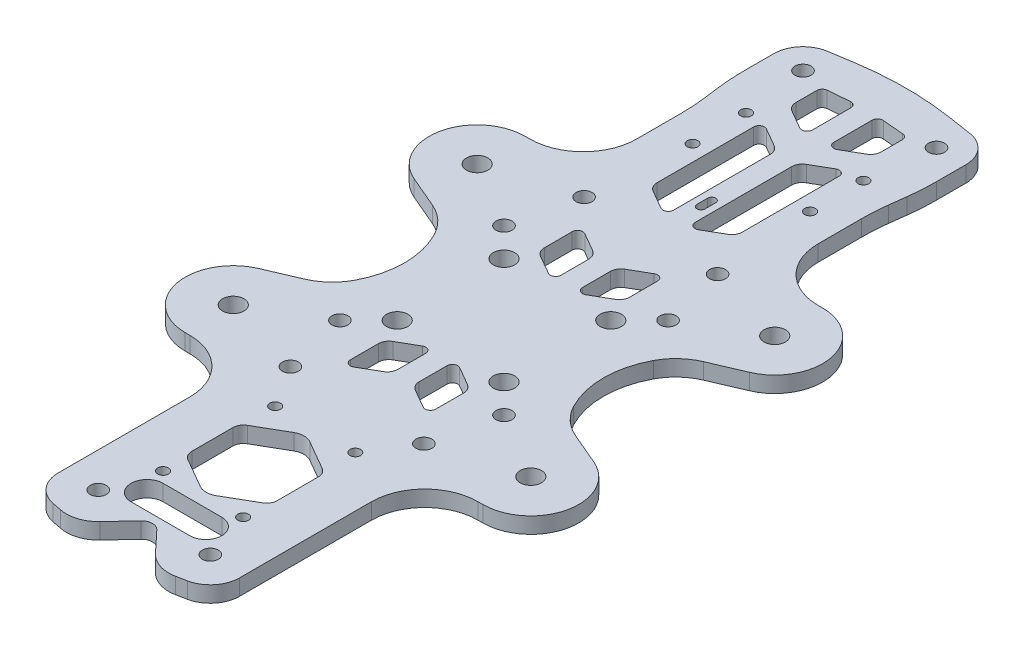
SolidWorks part; units mm, degrees
other "Markup1"
sketch "Sketch3" plane through (-36.8644, 3, -75.3176) normal (0, 1, 0) x (1, 0, 0)
material "Thornel Mat VMA"
ref_plane "Front Plane" through (0, 0, 0) normal (0, 0, 1) x (1, 0, 0)
ref_plane "Top Plane" through (0, 0, 0) normal (0, 1, 0) x (1, 0, 0)
ref_plane "Right Plane" through (0, 0, 0) normal (1, 0, 0) x (0, 0, -1)
sketch "Sketch1" plane through (0, 0, 0) normal (0, 1, 0) x (1, 0, 0)
  line L0 (7.0144, -13.8425) -> (3.5179, -11.8157)
  line L1 (-1.9927, -17.8721) -> (-1.9837, -12.6721)
  line L2 (-6.9856, 13.8181) -> (-3.4821, 11.8035)
  line L3 (2.0122, 17.9008) -> (2.0164, 12.6801)
  line L4 (2, 51.8812) -> (2, 33.7679)
  line L5 (-7, 34.9226) -> (-3.5, 32.9019)
  line L6 (3.5, 58.9019) -> (7, 60.9226)
  line L7 (-7, 60.9226) -> (-3.5, 58.9019)
  line L8 (-1.5, -37.866) -> (-7, -41.0415)
  line L9 (-6.6638, -69.1081) -> (-2.9181, -65.1127)
  line L10 (2.0164, -12.6801) -> (2.0122, -17.9008)
  line L11 (3, -19.6132) -> (6.5, -21.634)
  line L12 (8.002, -20.7686) -> (8.0113, -15.5764)
  line L13 (-3.4821, -11.8035) -> (-6.9856, -13.8181)
  line L14 (-7.9886, -15.5483) -> (-7.9977, -20.7675)
  line L15 (-6.5, -21.634) -> (-3, -19.6133)
  line L16 (-1.9837, 12.6721) -> (-1.9927, 17.8721)
  line L17 (-3, 19.6133) -> (-6.5, 21.634)
  line L18 (-7.9977, 20.7675) -> (-7.9886, 15.5483)
  line L19 (3.5179, 11.8157) -> (7.0144, 13.8425)
  line L20 (8.0113, 15.5764) -> (8.002, 20.7686)
  line L21 (6.5, 21.634) -> (3, 19.6132)
  line L22 (3.5, 32.9019) -> (7, 34.9226)
  line L23 (8, 36.6547) -> (8, 54.7679)
  line L24 (6.5, 55.634) -> (3, 53.6132)
  line L25 (-2, 33.7679) -> (-2, 51.8812)
  line L26 (-3, 53.6133) -> (-6.5, 55.634)
  line L27 (-8, 54.7679) -> (-8, 36.6546)
  line L28 (8, 62.6547) -> (8, 66.5946)
  line L29 (7.0872, 67.5908) -> (3.0872, 67.9408)
  line L30 (2, 66.9446) -> (2, 59.7679)
  line L31 (-2, 59.7679) -> (-2, 66.9446)
  line L32 (-3.0872, 67.9408) -> (-7.0872, 67.5908)
  line L33 (-8, 66.5946) -> (-8, 62.6547)
  line L34 (-8, -42.7735) -> (-8, -50.4641)
  line L35 (-7, -52.1962) -> (-1.5, -55.3716)
  line L36 (1.5, -55.3716) -> (7, -52.1962)
  line L37 (8, -50.4641) -> (8, -42.7735)
  line L38 (7, -41.0415) -> (1.5, -37.866)
  line L39 (-12.1839, -69.9325) -> (-10.3636, -70.2952)
  line L40 (-15, -41.84) -> (-15, -66.5)
  line L41 (-27.8644, -29.84) -> (-27, -29.84)
  line L42 (-24.6147, -13.8367) -> (-30.6171, -16.404)
  line L43 (-30.6171, 16.404) -> (-24.6147, 13.8367)
  line L44 (-26.9944, 29.84) -> (-27.8644, 29.84)
  line L45 (-14.9906, 49.9801) -> (-14.9944, 41.8344)
  line L46 (-15.6838, 58.0267) -> (-15.3029, 54.9969)
  line L47 (-16, 68.4976) -> (-15.9961, 62.9879)
  line L48 (-8.6637, 72.6434) -> (-13.0415, 71.9578)
  line L49 (13.0415, 71.9578) -> (8.6635, 72.6434)
  line L50 (15.9961, 62.9879) -> (15.9999, 68.4976)
  line L51 (15.3029, 54.9969) -> (15.6838, 58.0267)
  line L52 (14.9944, 41.8344) -> (14.9906, 49.98)
  line L53 (27.8644, 29.84) -> (26.9944, 29.84)
  line L54 (24.6147, 13.8367) -> (30.6171, 16.404)
  line L55 (30.6171, -16.404) -> (24.6147, -13.8367)
  line L56 (27, -29.84) -> (27.8644, -29.84)
  line L57 (15, -66.5) -> (15, -41.84)
  line L58 (10.3636, -70.2952) -> (12.1839, -69.9325)
  line L59 (2.9181, -65.1127) -> (6.6638, -69.1081)
  circle A0 centre (15.365, 15.365) radius 1.5
  circle A1 centre (15.365, -15.365) radius 1.5
  circle A2 centre (-15.365, -15.365) radius 1.5
  circle A3 centre (-15.365, 15.365) radius 1.5
  circle A4 centre (27.8644, -22.84) radius 2
  circle A5 centre (27.8644, 22.84) radius 2
  circle A6 centre (10.5, -65.5) radius 1.5
  circle A7 centre (-10, 10) radius 2
  circle A8 centre (-10, -10) radius 2
  circle A9 centre (-10.5, -65.5) radius 1.5
  circle A10 centre (-27.8644, -22.84) radius 2
  circle A11 centre (-27.8644, 22.84) radius 2
  circle A12 centre (12.5, 68.5) radius 1.5
  circle A13 centre (-12.5, 68.5) radius 1.5
  circle A14 centre (-10, -36.5) radius 1
  circle A15 centre (12.5, 27.5) radius 1.5
  circle A16 centre (-10, -56.5) radius 1
  circle A17 centre (-12.5, 27.5) radius 1.5
  circle A18 centre (12.5, -27.5) radius 1.5
  circle A19 centre (10, -36.5) radius 1
  circle A20 centre (-12.5, -27.5) radius 1.5
  circle A21 centre (10, -56.5) radius 1
  circle A22 centre (10, 10) radius 2
  circle A23 centre (10, -10) radius 2
  arc A24 (3.5179, -11.8157) -> (2.0164, -12.6801) centre (3.0164, -12.6808) ccw
  arc A25 (2.0122, -17.9008) -> (3, -19.6132) centre (3.9878, -17.9024) ccw
  arc A26 (6.5, -21.634) -> (8.002, -20.7686) centre (7.0007, -20.7668) ccw
  arc A27 (8.0113, -15.5764) -> (7.0144, -13.8425) centre (6.0113, -15.5728) ccw
  arc A28 (-1.9837, -12.6721) -> (-3.4821, -11.8035) centre (-2.9836, -12.6704) ccw
  arc A29 (-6.9856, -13.8181) -> (-7.9886, -15.5483) centre (-5.9887, -15.5518) ccw
  arc A30 (-7.9977, -20.7675) -> (-6.5, -21.634) centre (-6.9992, -20.7693) ccw
  arc A31 (-3, -19.6133) -> (-1.9927, -17.8721) centre (-4.0073, -17.8686) ccw
  arc A32 (-3.4821, 11.8035) -> (-1.9837, 12.6721) centre (-2.9836, 12.6704) ccw
  arc A33 (-1.9927, 17.8721) -> (-3, 19.6133) centre (-4.0073, 17.8686) ccw
  arc A34 (-6.5, 21.634) -> (-7.9977, 20.7675) centre (-6.9992, 20.7693) ccw
  arc A35 (-7.9886, 15.5483) -> (-6.9856, 13.8181) centre (-5.9887, 15.5518) ccw
  arc A36 (2.0164, 12.6801) -> (3.5179, 11.8157) centre (3.0164, 12.6808) ccw
  arc A37 (7.0144, 13.8425) -> (8.0113, 15.5764) centre (6.0113, 15.5728) ccw
  arc A38 (8.002, 20.7686) -> (6.5, 21.634) centre (7.0007, 20.7668) ccw
  arc A39 (3, 19.6132) -> (2.0122, 17.9008) centre (3.9878, 17.9024) ccw
  arc A40 (2, 33.7679) -> (3.5, 32.9019) centre (3, 33.7679) ccw
  arc A41 (7, 34.9226) -> (8, 36.6547) centre (6, 36.6547) ccw
  arc A42 (8, 54.7679) -> (6.5, 55.634) centre (7, 54.7679) ccw
  arc A43 (3, 53.6132) -> (2, 51.8812) centre (4, 51.8812) ccw
  arc A44 (-3.5, 32.9019) -> (-2, 33.7679) centre (-3, 33.7679) ccw
  arc A45 (-2, 51.8812) -> (-3, 53.6133) centre (-4, 51.8812) ccw
  arc A46 (-6.5, 55.634) -> (-8, 54.7679) centre (-7, 54.7679) ccw
  arc A47 (-8, 36.6546) -> (-7, 34.9226) centre (-6, 36.6546) ccw
  arc A48 (7, 60.9226) -> (8, 62.6547) centre (6, 62.6547) ccw
  arc A49 (8, 66.5946) -> (7.0872, 67.5908) centre (7, 66.5946) ccw
  arc A50 (3.0872, 67.9408) -> (2, 66.9446) centre (3, 66.9446) ccw
  arc A51 (2, 59.7679) -> (3.5, 58.9019) centre (3, 59.7679) ccw
  arc A52 (-3.5, 58.9019) -> (-2, 59.7679) centre (-3, 59.7679) ccw
  arc A53 (-2, 66.9446) -> (-3.0872, 67.9408) centre (-3, 66.9446) ccw
  arc A54 (-7.0872, 67.5908) -> (-8, 66.5946) centre (-7, 66.5946) ccw
  arc A55 (-8, 62.6547) -> (-7, 60.9226) centre (-6, 62.6547) ccw
  arc A56 (-7, -41.0415) -> (-8, -42.7735) centre (-6, -42.7735) ccw
  arc A57 (-8, -50.4641) -> (-7, -52.1962) centre (-6, -50.4641) ccw
  arc A58 (-1.5, -55.3716) -> (1.5, -55.3716) centre (0, -52.7735) ccw
  arc A59 (7, -52.1962) -> (8, -50.4641) centre (6, -50.4641) ccw
  arc A60 (8, -42.7735) -> (7, -41.0415) centre (6, -42.7735) ccw
  arc A61 (1.5, -37.866) -> (-1.5, -37.866) centre (0, -40.4641) ccw
  arc A62 (-10.3636, -70.2952) -> (-6.6638, -69.1081) centre (-9.582, -66.3723) ccw
  arc A63 (-15, -66.5) -> (-12.1839, -69.9325) centre (-11.5, -66.5) ccw
  arc A64 (-15, -41.84) -> (-27, -29.84) centre (-27, -41.84) ccw
  arc A65 (-30.6171, -16.404) -> (-27.8644, -29.84) centre (-27.8644, -22.84) ccw
  arc A66 (-24.6147, -13.8367) -> (-18.7242, -8.4106) centre (-29.3336, -2.8035) ccw
  arc A67 (-18.7242, -8.4106) -> (-18.7242, 8.4106) centre (-34.6384, 0) ccw
  arc A68 (-18.7242, 8.4106) -> (-24.6147, 13.8367) centre (-29.3336, 2.8035) ccw
  arc A69 (-27.8644, 29.84) -> (-30.6171, 16.404) centre (-27.8644, 22.84) ccw
  arc A70 (-26.9944, 29.84) -> (-14.9944, 41.8344) centre (-26.9944, 41.84) ccw
  arc A71 (-14.9906, 49.9801) -> (-15.3029, 54.9969) centre (-54.9906, 50.008) ccw
  arc A72 (-15.9961, 62.9879) -> (-15.6838, 58.0267) centre (24.0039, 63.0156) ccw
  arc A73 (-13.0415, 71.9578) -> (-16, 68.4976) centre (-12.5, 68.5) ccw
  arc A74 (8.6635, 72.6434) -> (-8.6637, 72.6434) centre (-0.0001, 17.3176) ccw
  arc A75 (15.9999, 68.4976) -> (13.0415, 71.9578) centre (12.5, 68.5) ccw
  arc A76 (15.6838, 58.0267) -> (15.9961, 62.9879) centre (-24.0039, 63.0156) ccw
  arc A77 (15.3029, 54.9969) -> (14.9906, 49.98) centre (54.9906, 50.008) ccw
  arc A78 (14.9944, 41.8344) -> (26.9944, 29.84) centre (26.9944, 41.84) ccw
  arc A79 (30.6171, 16.404) -> (27.8644, 29.84) centre (27.8644, 22.84) ccw
  arc A80 (24.6147, 13.8367) -> (18.7242, 8.4106) centre (29.3336, 2.8035) ccw
  arc A81 (18.7242, 8.4106) -> (18.7242, -8.4106) centre (34.6384, 0) ccw
  arc A82 (18.7242, -8.4106) -> (24.6147, -13.8367) centre (29.3336, -2.8035) ccw
  arc A83 (27.8644, -29.84) -> (30.6171, -16.404) centre (27.8644, -22.84) ccw
  arc A84 (27, -29.84) -> (15, -41.84) centre (27, -41.84) ccw
  arc A85 (12.1839, -69.9325) -> (15, -66.5) centre (11.5, -66.5) ccw
  arc A86 (6.6638, -69.1081) -> (10.3636, -70.2952) centre (9.582, -66.3723) ccw
  arc A87 (2.9181, -65.1127) -> (-2.9181, -65.1127) centre (0, -67.8485) ccw
sketch "Sketch2" plane through (0, 0, 0) normal (0, 1, 0) x (1, 0, 0)
  line L0 (-3.5, 32.9019) -> (3.5, 32.9019) construction
  line L5 (0, 38.9019) -> (0, 36.9019) construction
  line L7 (0.75, 38.9019) -> (0.75, 36.9019)
  line L8 (-0.75, 38.9019) -> (-0.75, 36.9019)
  line L9 (0, 0) -> (-0.0001, 75.3176) construction
  line L10 (0, 0) -> (0, -65.8485) construction
  line L11 (-18.6384, 0) -> (18.6384, 0) construction
  line L12 (-5.5, -61.3485) -> (5.5, -61.3485) construction
  line L13 (-5.5, -58.3485) -> (5.5, -58.3485)
  line L14 (-5.5, -64.3485) -> (5.5, -64.3485)
  line L15 (-14.0001, 51.3176) -> (13.9999, 51.3176) construction
  line L16 (-14.0001, 64.3176) -> (13.9999, 64.3176) construction
  line L17 (-14.0001, 64.3176) -> (-14.0001, 44.3176) construction
  line L18 (-14.0001, 44.3176) -> (13.9999, 44.3176) construction
  line L19 (13.9999, 64.3176) -> (13.9999, 44.3176) construction
  line L20 (-14.0001, 64.3176) -> (13.9999, 44.3176) construction
  line L21 (-14.0001, 44.3176) -> (13.9999, 64.3176) construction
  line L22 (-11.0001, 46.3176) -> (10.9999, 46.3176) construction
  line L513 (7, -41.0415) -> (1.5, -37.866) construction
  line L514 (-1.5, -37.866) -> (-7, -41.0415) construction
  line L515 (1.5, -55.3716) -> (7, -52.1962) construction
  line L516 (8, -50.4641) -> (8, -42.7735) construction
  line L517 (-8, -42.7735) -> (-8, -50.4641) construction
  line L518 (-7, -52.1962) -> (-1.5, -55.3716) construction
  line L519 (3, -19.6132) -> (6.5, -21.634) construction
  line L520 (7.0144, -13.8425) -> (3.5179, -11.8157) construction
  line L521 (8.002, -20.7686) -> (8.0113, -15.5764) construction
  line L522 (2.0164, -12.6801) -> (2.0122, -17.9008) construction
  line L523 (-6.5, -21.634) -> (-3, -19.6133) construction
  line L524 (-7.9886, -15.5483) -> (-7.9977, -20.7675) construction
  line L525 (-3.4821, -11.8035) -> (-6.9856, -13.8181) construction
  line L526 (-1.9927, -17.8721) -> (-1.9837, -12.6721) construction
  line L527 (3.5179, 11.8157) -> (7.0144, 13.8425) construction
  line L528 (8.0113, 15.5764) -> (8.002, 20.7686) construction
  line L529 (6.5, 21.634) -> (3, 19.6132) construction
  line L530 (-3, 19.6133) -> (-6.5, 21.634) construction
  line L531 (-7.9977, 20.7675) -> (-7.9886, 15.5483) construction
  line L532 (-1.9837, 12.6721) -> (-1.9927, 17.8721) construction
  line L533 (2.0122, 17.9008) -> (2.0164, 12.6801) construction
  line L534 (-6.9856, 13.8181) -> (-3.4821, 11.8035) construction
  line L535 (13.3509, 73.9337) -> (8.9729, 74.6193)
  line L536 (-8.9731, 74.6193) -> (-13.3509, 73.9338)
  line L537 (-18, 68.4962) -> (-17.9961, 62.9865)
  line L538 (-17.6682, 57.7773) -> (-17.2873, 54.7475)
  line L539 (17.9961, 62.9865) -> (17.9999, 68.4962)
  line L540 (17.2873, 54.7474) -> (17.6682, 57.7773)
  line L541 (-16.9906, 49.981) -> (-16.9944, 41.8353)
  line L542 (16.9944, 41.8353) -> (16.9906, 49.9814)
  line L543 (27.8644, 31.84) -> (26.9944, 31.84)
  line L544 (25.4012, 11.9979) -> (31.4036, 14.5651)
  line L545 (31.4036, -14.5651) -> (25.4012, -11.9979)
  line L546 (27, -31.84) -> (27.8644, -31.84)
  line L547 (17, -66.5) -> (17, -41.84)
  line L548 (10.7545, -72.2567) -> (12.5748, -71.894)
  line L549 (1.4591, -66.4806) -> (5.2048, -70.476)
  line L550 (-5.2048, -70.476) -> (-1.4591, -66.4806)
  line L551 (-12.5748, -71.894) -> (-10.7545, -72.2567)
  line L552 (-17, -41.84) -> (-17, -66.5)
  line L553 (-27.8644, -31.84) -> (-27, -31.84)
  line L554 (-25.4012, -11.9979) -> (-31.4036, -14.5651)
  line L555 (-31.4036, 14.5651) -> (-25.4012, 11.9979)
  line L556 (-26.9944, 31.84) -> (-27.8644, 31.84)
  line L557 (13.3509, 73.9337) -> (8.9729, 74.6193)
  line L558 (-8.9731, 74.6193) -> (-13.3509, 73.9338)
  line L559 (-18, 68.4962) -> (-17.9961, 62.9865)
  line L560 (-17.6682, 57.7773) -> (-17.2873, 54.7475)
  line L561 (17.9961, 62.9865) -> (17.9999, 68.4962)
  line L562 (17.2873, 54.7474) -> (17.6682, 57.7773)
  line L563 (-16.9906, 49.981) -> (-16.9944, 41.8353)
  line L564 (16.9944, 41.8353) -> (16.9906, 49.9814)
  line L565 (27.8644, 31.84) -> (26.9944, 31.84)
  line L566 (25.4012, 11.9979) -> (31.4036, 14.5651)
  line L567 (31.4036, -14.5651) -> (25.4012, -11.9979)
  line L568 (27, -31.84) -> (27.8644, -31.84)
  line L569 (17, -66.5) -> (17, -41.84)
  line L570 (10.7545, -72.2567) -> (12.5748, -71.894)
  line L571 (1.4591, -66.4806) -> (5.2048, -70.476)
  line L572 (-5.2048, -70.476) -> (-1.4591, -66.4806)
  line L573 (-12.5748, -71.894) -> (-10.7545, -72.2567)
  line L574 (-17, -41.84) -> (-17, -66.5)
  line L575 (-27.8644, -31.84) -> (-27, -31.84)
  line L576 (-25.4012, -11.9979) -> (-31.4036, -14.5651)
  line L577 (-31.4036, 14.5651) -> (-25.4012, 11.9979)
  line L578 (-26.9944, 31.84) -> (-27.8644, 31.84)
  line L579 (3.5, 32.9019) -> (7, 34.9226) construction
  line L580 (-7, 34.9226) -> (-3.5, 32.9019) construction
  line L581 (8, 36.6547) -> (8, 54.7679) construction
  line L582 (6.5, 55.634) -> (3, 53.6132) construction
  line L583 (-3, 53.6133) -> (-6.5, 55.634) construction
  line L584 (-2, 33.7679) -> (-2, 51.8812) construction
  line L585 (2, 51.8812) -> (2, 33.7679) construction
  line L586 (-8, 54.7679) -> (-8, 36.6546) construction
  line L587 (3.5, 58.9019) -> (7, 60.9226) construction
  line L588 (8, 62.6547) -> (8, 66.5946) construction
  line L589 (7.0872, 67.5908) -> (3.0872, 67.9408) construction
  line L590 (2, 66.9446) -> (2, 59.7679) construction
  line L591 (-7, 60.9226) -> (-3.5, 58.9019) construction
  line L592 (-2, 59.7679) -> (-2, 66.9446) construction
  line L593 (-3.0872, 67.9408) -> (-7.0872, 67.5908) construction
  line L594 (-8, 66.5946) -> (-8, 62.6547) construction
  line L595 (7, -41.0415) -> (1.5, -37.866)
  line L596 (-1.5, -37.866) -> (-7, -41.0415)
  line L597 (1.5, -55.3716) -> (7, -52.1962)
  line L598 (8, -50.4641) -> (8, -42.7735)
  line L599 (-8, -42.7735) -> (-8, -50.4641)
  line L600 (-7, -52.1962) -> (-1.5, -55.3716)
  line L601 (3, -19.6132) -> (6.5, -21.634)
  line L602 (7.0144, -13.8425) -> (3.5179, -11.8157)
  line L603 (8.002, -20.7686) -> (8.0113, -15.5764)
  line L604 (2.0164, -12.6801) -> (2.0122, -17.9008)
  line L605 (-6.5, -21.634) -> (-3, -19.6133)
  line L606 (-7.9886, -15.5483) -> (-7.9977, -20.7675)
  line L607 (-3.4821, -11.8035) -> (-6.9856, -13.8181)
  line L608 (-1.9927, -17.8721) -> (-1.9837, -12.6721)
  line L609 (3.5179, 11.8157) -> (7.0144, 13.8425)
  line L610 (8.0113, 15.5764) -> (8.002, 20.7686)
  line L611 (6.5, 21.634) -> (3, 19.6132)
  line L612 (-3, 19.6133) -> (-6.5, 21.634)
  line L613 (-7.9977, 20.7675) -> (-7.9886, 15.5483)
  line L614 (-1.9837, 12.6721) -> (-1.9927, 17.8721)
  line L615 (2.0122, 17.9008) -> (2.0164, 12.6801)
  line L616 (-6.9856, 13.8181) -> (-3.4821, 11.8035)
  line L617 (3.5, 32.9019) -> (7, 34.9226)
  line L618 (-7, 34.9226) -> (-3.5, 32.9019)
  line L619 (8, 36.6547) -> (8, 54.7679)
  line L620 (6.5, 55.634) -> (3, 53.6132)
  line L621 (-3, 53.6133) -> (-6.5, 55.634)
  line L622 (-2, 33.7679) -> (-2, 51.8812)
  line L623 (2, 51.8812) -> (2, 33.7679)
  line L624 (-8, 54.7679) -> (-8, 36.6546)
  line L625 (3.5, 58.9019) -> (7, 60.9226)
  line L626 (8, 62.6547) -> (8, 66.5946)
  line L627 (7.0872, 67.5908) -> (3.0872, 67.9408)
  line L628 (2, 66.9446) -> (2, 59.7679)
  line L629 (-7, 60.9226) -> (-3.5, 58.9019)
  line L630 (-2, 59.7679) -> (-2, 66.9446)
  line L631 (-3.0872, 67.9408) -> (-7.0872, 67.5908)
  line L632 (-8, 66.5946) -> (-8, 62.6547)
  arc A1 (0.75, 38.9019) -> (-0.75, 38.9019) centre (0, 38.9019) ccw
  arc A2 (-0.75, 36.9019) -> (0.75, 36.9019) centre (0, 36.9019) ccw
  circle A3 centre (-12.5, 68.5) radius 2.75 construction
  circle A4 centre (12.4998, 68.5) radius 2.75 construction
  circle A5 centre (-7.5, -35.3485) radius 1
  circle A6 centre (-7.5, -56.3485) radius 1
  circle A7 centre (7.5, -35.3485) radius 1
  circle A8 centre (7.5, -56.3485) radius 1
  arc A9 (-5.5, -58.3485) -> (-5.5, -64.3485) centre (-5.5, -61.3485) ccw
  arc A10 (5.5, -64.3485) -> (5.5, -58.3485) centre (5.5, -61.3485) ccw
  circle A11 centre (-10.5, -65.5) radius 2.75 construction
  circle A12 centre (10.5, -65.5) radius 2.75 construction
  circle A16 centre (-11.0001, 46.3176) radius 1
  circle A17 centre (10.9999, 46.3176) radius 1
  circle A18 centre (10.9999, 56.3176) radius 1
  circle A19 centre (-11.0001, 56.3176) radius 1
  arc A666 (8, -42.7735) -> (7, -41.0415) centre (6, -42.7735) ccw construction
  arc A667 (1.5, -37.866) -> (-1.5, -37.866) centre (0, -40.4641) ccw construction
  arc A668 (-7, -41.0415) -> (-8, -42.7735) centre (-6, -42.7735) ccw construction
  arc A669 (-8, -50.4641) -> (-7, -52.1962) centre (-6, -50.4641) ccw construction
  arc A670 (-1.5, -55.3716) -> (1.5, -55.3716) centre (0, -52.7735) ccw construction
  arc A671 (7, -52.1962) -> (8, -50.4641) centre (6, -50.4641) ccw construction
  circle A674 centre (10.5, -65.5) radius 1.5 construction
  circle A675 centre (-10.5, -65.5) radius 1.5 construction
  arc A676 (6.5, -21.634) -> (8.002, -20.7686) centre (7.0007, -20.7668) ccw construction
  arc A677 (2.0122, -17.9008) -> (3, -19.6132) centre (3.9878, -17.9024) ccw construction
  arc A678 (3.5179, -11.8157) -> (2.0164, -12.6801) centre (3.0164, -12.6808) ccw construction
  arc A679 (8.0113, -15.5764) -> (7.0144, -13.8425) centre (6.0113, -15.5728) ccw construction
  arc A680 (-3, -19.6133) -> (-1.9927, -17.8721) centre (-4.0073, -17.8686) ccw construction
  arc A681 (-7.9977, -20.7675) -> (-6.5, -21.634) centre (-6.9992, -20.7693) ccw construction
  arc A682 (-6.9856, -13.8181) -> (-7.9886, -15.5483) centre (-5.9887, -15.5518) ccw construction
  arc A683 (-1.9837, -12.6721) -> (-3.4821, -11.8035) centre (-2.9836, -12.6704) ccw construction
  circle A684 centre (10, -10) radius 2 construction
  circle A685 centre (15.365, -15.365) radius 1.5 construction
  circle A686 centre (27.8644, -22.84) radius 2 construction
  circle A687 centre (12.5, -27.5) radius 1.5 construction
  circle A690 centre (-10, -10) radius 2 construction
  circle A691 centre (-15.365, -15.365) radius 1.5 construction
  arc A692 (8.9729, 74.6193) -> (-8.9731, 74.6193) centre (-0.0001, 17.3176) ccw
  arc A693 (-13.3509, 73.9338) -> (-18, 68.4962) centre (-12.5, 68.5) ccw
  arc A694 (-17.9961, 62.9865) -> (-17.6682, 57.7773) centre (24.0039, 63.0156) ccw
  arc A695 (17.9999, 68.4962) -> (13.3509, 73.9337) centre (12.5, 68.5) ccw
  arc A696 (17.6682, 57.7773) -> (17.9961, 62.9865) centre (-24.0039, 63.0156) ccw
  arc A697 (-16.9906, 49.981) -> (-17.2873, 54.7475) centre (-54.9906, 50.008) ccw
  arc A698 (17.2873, 54.7474) -> (16.9906, 49.9814) centre (54.9906, 50.008) ccw
  arc A699 (16.9944, 41.8353) -> (26.9944, 31.84) centre (26.9944, 41.84) ccw
  arc A700 (31.4036, 14.5651) -> (27.8644, 31.84) centre (27.8644, 22.84) ccw
  arc A701 (25.4012, 11.9979) -> (20.4924, 7.4761) centre (29.3336, 2.8035) ccw
  arc A702 (20.4924, 7.4761) -> (20.4924, -7.4761) centre (34.6384, 0) ccw
  arc A703 (20.4924, -7.4761) -> (25.4012, -11.9979) centre (29.3336, -2.8035) ccw
  arc A704 (27.8644, -31.84) -> (31.4036, -14.5651) centre (27.8644, -22.84) ccw
  arc A705 (27, -31.84) -> (17, -41.84) centre (27, -41.84) ccw
  arc A706 (12.5748, -71.894) -> (17, -66.5) centre (11.5, -66.5) ccw
  arc A707 (5.2048, -70.476) -> (10.7545, -72.2567) centre (9.582, -66.3723) ccw
  arc A708 (1.4591, -66.4806) -> (-1.4591, -66.4806) centre (0, -67.8485) ccw
  arc A709 (-10.7545, -72.2567) -> (-5.2048, -70.476) centre (-9.582, -66.3723) ccw
  arc A710 (-17, -66.5) -> (-12.5748, -71.894) centre (-11.5, -66.5) ccw
  arc A711 (-17, -41.84) -> (-27, -31.84) centre (-27, -41.84) ccw
  arc A712 (-31.4036, -14.5651) -> (-27.8644, -31.84) centre (-27.8644, -22.84) ccw
  arc A713 (-25.4012, -11.9979) -> (-20.4924, -7.4761) centre (-29.3336, -2.8035) ccw
  arc A714 (-20.4924, -7.4761) -> (-20.4924, 7.4761) centre (-34.6384, 0) ccw
  arc A715 (-20.4924, 7.4761) -> (-25.4012, 11.9979) centre (-29.3336, 2.8035) ccw
  arc A716 (-27.8644, 31.84) -> (-31.4036, 14.5651) centre (-27.8644, 22.84) ccw
  arc A717 (-26.9944, 31.84) -> (-16.9944, 41.8353) centre (-26.9944, 41.84) ccw
  arc A718 (8.9729, 74.6193) -> (-8.9731, 74.6193) centre (-0.0001, 17.3176) ccw
  arc A719 (-13.3509, 73.9338) -> (-18, 68.4962) centre (-12.5, 68.5) ccw
  arc A720 (-17.9961, 62.9865) -> (-17.6682, 57.7773) centre (24.0039, 63.0156) ccw
  arc A721 (17.9999, 68.4962) -> (13.3509, 73.9337) centre (12.5, 68.5) ccw
  arc A722 (17.6682, 57.7773) -> (17.9961, 62.9865) centre (-24.0039, 63.0156) ccw
  arc A723 (-16.9906, 49.981) -> (-17.2873, 54.7475) centre (-54.9906, 50.008) ccw
  arc A724 (17.2873, 54.7474) -> (16.9906, 49.9814) centre (54.9906, 50.008) ccw
  arc A725 (16.9944, 41.8353) -> (26.9944, 31.84) centre (26.9944, 41.84) ccw
  arc A726 (31.4036, 14.5651) -> (27.8644, 31.84) centre (27.8644, 22.84) ccw
  arc A727 (25.4012, 11.9979) -> (20.4924, 7.4761) centre (29.3336, 2.8035) ccw
  arc A728 (20.4924, 7.4761) -> (20.4924, -7.4761) centre (34.6384, 0) ccw
  arc A729 (20.4924, -7.4761) -> (25.4012, -11.9979) centre (29.3336, -2.8035) ccw
  arc A730 (27.8644, -31.84) -> (31.4036, -14.5651) centre (27.8644, -22.84) ccw
  arc A731 (27, -31.84) -> (17, -41.84) centre (27, -41.84) ccw
  arc A732 (12.5748, -71.894) -> (17, -66.5) centre (11.5, -66.5) ccw
  arc A733 (5.2048, -70.476) -> (10.7545, -72.2567) centre (9.582, -66.3723) ccw
  arc A734 (1.4591, -66.4806) -> (-1.4591, -66.4806) centre (0, -67.8485) ccw
  arc A735 (-10.7545, -72.2567) -> (-5.2048, -70.476) centre (-9.582, -66.3723) ccw
  arc A736 (-17, -66.5) -> (-12.5748, -71.894) centre (-11.5, -66.5) ccw
  arc A737 (-17, -41.84) -> (-27, -31.84) centre (-27, -41.84) ccw
  arc A738 (-31.4036, -14.5651) -> (-27.8644, -31.84) centre (-27.8644, -22.84) ccw
  arc A739 (-25.4012, -11.9979) -> (-20.4924, -7.4761) centre (-29.3336, -2.8035) ccw
  arc A740 (-20.4924, -7.4761) -> (-20.4924, 7.4761) centre (-34.6384, 0) ccw
  arc A741 (-20.4924, 7.4761) -> (-25.4012, 11.9979) centre (-29.3336, 2.8035) ccw
  arc A742 (-27.8644, 31.84) -> (-31.4036, 14.5651) centre (-27.8644, 22.84) ccw
  arc A743 (-26.9944, 31.84) -> (-16.9944, 41.8353) centre (-26.9944, 41.84) ccw
  circle A744 centre (-12.5, -27.5) radius 1.5 construction
  circle A745 centre (-27.8644, -22.84) radius 2 construction
  circle A746 centre (27.8644, 22.84) radius 2 construction
  circle A747 centre (15.365, 15.365) radius 1.5 construction
  circle A748 centre (10, 10) radius 2 construction
  arc A749 (2.0164, 12.6801) -> (3.5179, 11.8157) centre (3.0164, 12.6808) ccw construction
  arc A750 (7.0144, 13.8425) -> (8.0113, 15.5764) centre (6.0113, 15.5728) ccw construction
  arc A751 (8.002, 20.7686) -> (6.5, 21.634) centre (7.0007, 20.7668) ccw construction
  arc A752 (3, 19.6132) -> (2.0122, 17.9008) centre (3.9878, 17.9024) ccw construction
  arc A753 (-1.9927, 17.8721) -> (-3, 19.6133) centre (-4.0073, 17.8686) ccw construction
  arc A754 (-6.5, 21.634) -> (-7.9977, 20.7675) centre (-6.9992, 20.7693) ccw construction
  arc A755 (-7.9886, 15.5483) -> (-6.9856, 13.8181) centre (-5.9887, 15.5518) ccw construction
  arc A756 (-3.4821, 11.8035) -> (-1.9837, 12.6721) centre (-2.9836, 12.6704) ccw construction
  circle A757 centre (-10, 10) radius 2 construction
  circle A758 centre (-15.365, 15.365) radius 1.5 construction
  circle A759 centre (-27.8644, 22.84) radius 2 construction
  circle A760 centre (-12.5, 27.5) radius 1.5 construction
  circle A761 centre (12.5, 27.5) radius 1.5 construction
  arc A762 (7, 34.9226) -> (8, 36.6547) centre (6, 36.6547) ccw construction
  arc A763 (2, 33.7679) -> (3.5, 32.9019) centre (3, 33.7679) ccw construction
  arc A764 (-8, 36.6546) -> (-7, 34.9226) centre (-6, 36.6546) ccw construction
  arc A765 (-3.5, 32.9019) -> (-2, 33.7679) centre (-3, 33.7679) ccw construction
  arc A766 (8, 54.7679) -> (6.5, 55.634) centre (7, 54.7679) ccw construction
  arc A767 (3, 53.6132) -> (2, 51.8812) centre (4, 51.8812) ccw construction
  arc A768 (-2, 51.8812) -> (-3, 53.6133) centre (-4, 51.8812) ccw construction
  arc A769 (-6.5, 55.634) -> (-8, 54.7679) centre (-7, 54.7679) ccw construction
  arc A770 (2, 59.7679) -> (3.5, 58.9019) centre (3, 59.7679) ccw construction
  arc A771 (7, 60.9226) -> (8, 62.6547) centre (6, 62.6547) ccw construction
  arc A772 (8, 66.5946) -> (7.0872, 67.5908) centre (7, 66.5946) ccw construction
  arc A773 (3.0872, 67.9408) -> (2, 66.9446) centre (3, 66.9446) ccw construction
  arc A774 (-8, 62.6547) -> (-7, 60.9226) centre (-6, 62.6547) ccw construction
  arc A775 (-3.5, 58.9019) -> (-2, 59.7679) centre (-3, 59.7679) ccw construction
  arc A776 (-2, 66.9446) -> (-3.0872, 67.9408) centre (-3, 66.9446) ccw construction
  arc A777 (-7.0872, 67.5908) -> (-8, 66.5946) centre (-7, 66.5946) ccw construction
  circle A778 centre (-12.5, 68.5) radius 1.5 construction
  circle A779 centre (12.5, 68.5) radius 1.5 construction
  arc A780 (8, -42.7735) -> (7, -41.0415) centre (6, -42.7735) ccw
  arc A781 (1.5, -37.866) -> (-1.5, -37.866) centre (0, -40.4641) ccw
  arc A782 (-7, -41.0415) -> (-8, -42.7735) centre (-6, -42.7735) ccw
  arc A783 (-8, -50.4641) -> (-7, -52.1962) centre (-6, -50.4641) ccw
  arc A784 (-1.5, -55.3716) -> (1.5, -55.3716) centre (0, -52.7735) ccw
  arc A785 (7, -52.1962) -> (8, -50.4641) centre (6, -50.4641) ccw
  circle A788 centre (10.5, -65.5) radius 1.5
  circle A789 centre (-10.5, -65.5) radius 1.5
  arc A790 (6.5, -21.634) -> (8.002, -20.7686) centre (7.0007, -20.7668) ccw
  arc A791 (2.0122, -17.9008) -> (3, -19.6132) centre (3.9878, -17.9024) ccw
  arc A792 (3.5179, -11.8157) -> (2.0164, -12.6801) centre (3.0164, -12.6808) ccw
  arc A793 (8.0113, -15.5764) -> (7.0144, -13.8425) centre (6.0113, -15.5728) ccw
  arc A794 (-3, -19.6133) -> (-1.9927, -17.8721) centre (-4.0073, -17.8686) ccw
  arc A795 (-7.9977, -20.7675) -> (-6.5, -21.634) centre (-6.9992, -20.7693) ccw
  arc A796 (-6.9856, -13.8181) -> (-7.9886, -15.5483) centre (-5.9887, -15.5518) ccw
  arc A797 (-1.9837, -12.6721) -> (-3.4821, -11.8035) centre (-2.9836, -12.6704) ccw
  circle A798 centre (10, -10) radius 2
  circle A799 centre (15.365, -15.365) radius 1.5
  circle A800 centre (27.8644, -22.84) radius 2
  circle A801 centre (12.5, -27.5) radius 1.5
  circle A804 centre (-10, -10) radius 2
  circle A805 centre (-15.365, -15.365) radius 1.5
  circle A806 centre (-12.5, -27.5) radius 1.5
  circle A807 centre (-27.8644, -22.84) radius 2
  circle A808 centre (27.8644, 22.84) radius 2
  circle A809 centre (15.365, 15.365) radius 1.5
  circle A810 centre (10, 10) radius 2
  arc A811 (2.0164, 12.6801) -> (3.5179, 11.8157) centre (3.0164, 12.6808) ccw
  arc A812 (7.0144, 13.8425) -> (8.0113, 15.5764) centre (6.0113, 15.5728) ccw
  arc A813 (8.002, 20.7686) -> (6.5, 21.634) centre (7.0007, 20.7668) ccw
  arc A814 (3, 19.6132) -> (2.0122, 17.9008) centre (3.9878, 17.9024) ccw
  arc A815 (-1.9927, 17.8721) -> (-3, 19.6133) centre (-4.0073, 17.8686) ccw
  arc A816 (-6.5, 21.634) -> (-7.9977, 20.7675) centre (-6.9992, 20.7693) ccw
  arc A817 (-7.9886, 15.5483) -> (-6.9856, 13.8181) centre (-5.9887, 15.5518) ccw
  arc A818 (-3.4821, 11.8035) -> (-1.9837, 12.6721) centre (-2.9836, 12.6704) ccw
  circle A819 centre (-10, 10) radius 2
  circle A820 centre (-15.365, 15.365) radius 1.5
  circle A821 centre (-27.8644, 22.84) radius 2
  circle A822 centre (-12.5, 27.5) radius 1.5
  circle A823 centre (12.5, 27.5) radius 1.5
  arc A824 (7, 34.9226) -> (8, 36.6547) centre (6, 36.6547) ccw
  arc A825 (2, 33.7679) -> (3.5, 32.9019) centre (3, 33.7679) ccw
  arc A826 (-8, 36.6546) -> (-7, 34.9226) centre (-6, 36.6546) ccw
  arc A827 (-3.5, 32.9019) -> (-2, 33.7679) centre (-3, 33.7679) ccw
  arc A828 (8, 54.7679) -> (6.5, 55.634) centre (7, 54.7679) ccw
  arc A829 (3, 53.6132) -> (2, 51.8812) centre (4, 51.8812) ccw
  arc A830 (-2, 51.8812) -> (-3, 53.6133) centre (-4, 51.8812) ccw
  arc A831 (-6.5, 55.634) -> (-8, 54.7679) centre (-7, 54.7679) ccw
  arc A832 (2, 59.7679) -> (3.5, 58.9019) centre (3, 59.7679) ccw
  arc A833 (7, 60.9226) -> (8, 62.6547) centre (6, 62.6547) ccw
  arc A834 (8, 66.5946) -> (7.0872, 67.5908) centre (7, 66.5946) ccw
  arc A835 (3.0872, 67.9408) -> (2, 66.9446) centre (3, 66.9446) ccw
  arc A836 (-8, 62.6547) -> (-7, 60.9226) centre (-6, 62.6547) ccw
  arc A837 (-3.5, 58.9019) -> (-2, 59.7679) centre (-3, 59.7679) ccw
  arc A838 (-2, 66.9446) -> (-3.0872, 67.9408) centre (-3, 66.9446) ccw
  arc A839 (-7.0872, 67.5908) -> (-8, 66.5946) centre (-7, 66.5946) ccw
  circle A840 centre (-12.5, 68.5) radius 1.5
  circle A841 centre (12.5, 68.5) radius 1.5
  point P26 (0, 37.9019)
  point P72 (0, 0)
  point P75 (0, 32.9019)
  point P138 (0, -61.3485)
  point P165 (-0.0001, 54.3176)
  point P190 (-0.0001, 46.3176)
  dimension "D5" = 20
  dimension "D15" = 11
  dimension "D14" = 28
  dimension "D20" = 7
  dimension "D1" = 2
extrude "Boss-Extrude1" add sketch "Sketch2" along normal blind 3
